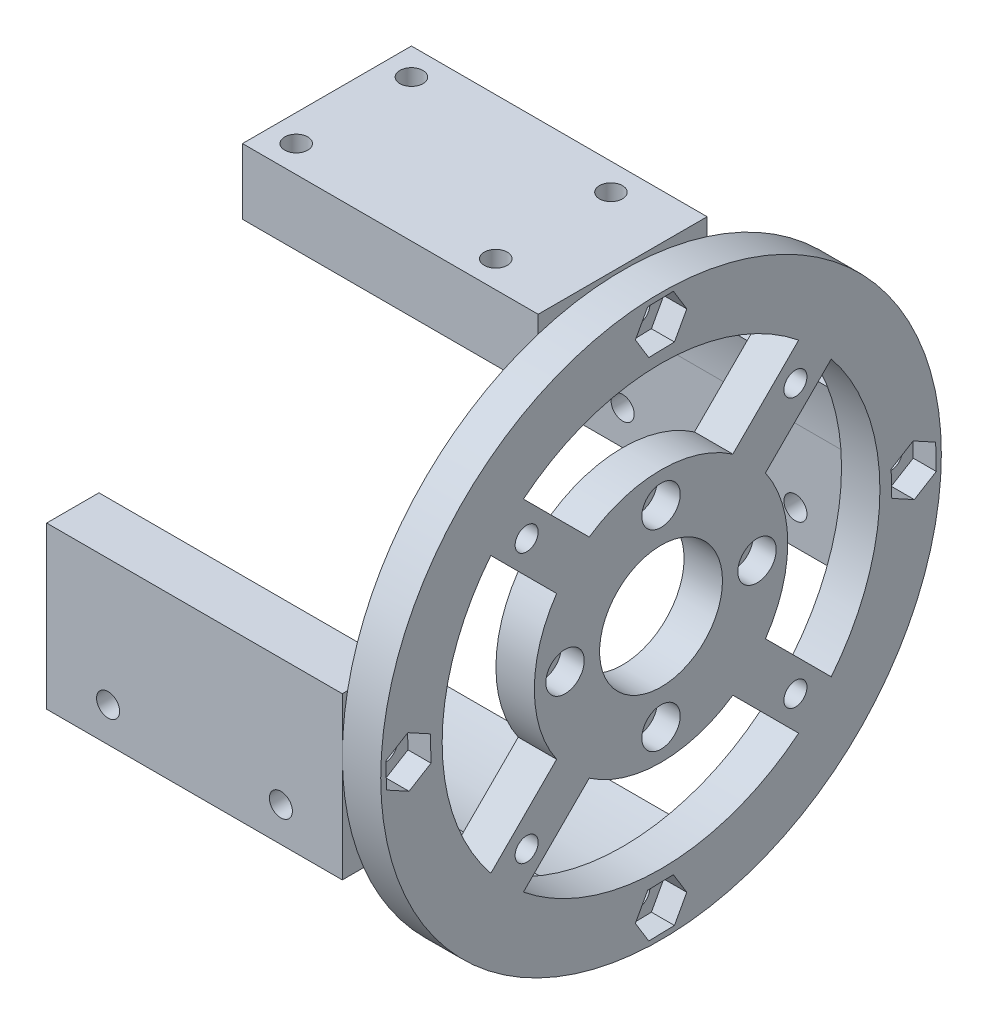
SolidWorks part; units mm, degrees
material "聚脂树脂"
ref_plane "前视基准面" through (0, 0, 0) normal (0, 0, 1) x (1, 0, 0)
ref_plane "上视基准面" through (0, 0, 0) normal (0, 1, 0) x (1, 0, 0)
ref_plane "右视基准面" through (0, 0, 0) normal (1, 0, 0) x (0, 0, -1)
sketch "草图1" plane through (0, 0, 0) normal (1, 0, 0) x (0, 0, -1)
  line L2 (13.5941, 9.3515) -> (22.1619, 17.9193)
  line L3 (9.3515, 13.5941) -> (17.9193, 22.1619)
  line L4 (13.5941, -9.3515) -> (22.1619, -17.9193)
  line L5 (9.3515, -13.5941) -> (17.9193, -22.1619)
  line L6 (-9.3515, -13.5941) -> (-17.9193, -22.1619)
  line L7 (-13.5941, -9.3515) -> (-22.1619, -17.9193)
  line L8 (-13.5941, 9.3515) -> (-22.1619, 17.9193)
  line L9 (-9.3515, 13.5941) -> (-17.9193, 22.1619)
  circle A0 centre (0, 0) radius 36.5
  circle A2 centre (0, 12.5) radius 1.55
  circle A3 centre (12.5, 0) radius 1.55
  circle A4 centre (0, -12.5) radius 1.55
  circle A5 centre (-12.5, 0) radius 1.55
  circle A6 centre (0, 0) radius 8
  arc A7 (17.9193, 22.1619) -> (-17.9193, 22.1619) centre (0, 0) ccw
  arc A8 (9.3515, 13.5941) -> (-9.3515, 13.5941) centre (0, 0) ccw
  arc A9 (-13.5941, 9.3515) -> (-13.5941, -9.3515) centre (0, 0) ccw
  arc A10 (-9.3515, -13.5941) -> (9.3515, -13.5941) centre (0, 0) ccw
  arc A14 (13.5941, -9.3515) -> (13.5941, 9.3515) centre (0, 0) ccw
  arc A15 (-22.1619, 17.9193) -> (-22.1619, -17.9193) centre (0, 0) ccw
  arc A16 (-17.9193, -22.1619) -> (17.9193, -22.1619) centre (0, 0) ccw
  arc A17 (22.1619, -17.9193) -> (22.1619, 17.9193) centre (0, 0) ccw
  point P15 (0, 0)
  point P37 (0, 0)
  dimension "73" = 73
  dimension "D3" = 3.1
  dimension "D5" = 16
  dimension "D6" = 57
  dimension "D7" = 33
  dimension "D4" = 4
  dimension "D11" = 4
extrude "凸台-拉伸1" add sketch "草图1" against normal blind 5
sketch "草图2" plane through (-5, 0, 0) normal (-1, 0, 0) x (0, 0, 1)
  line L0 (0, 30.5) -> (0, 36.5)
  line L1 (5.9179, 29.9204) -> (7.0821, 35.8063)
  line L2 (-7.0821, 35.8063) -> (-5.9179, 29.9204)
  line L3 (29.9025, -6.0076) -> (35.7885, -7.1718)
  line L4 (35.7885, 6.9924) -> (29.9025, 5.8282)
  line L5 (-6.0255, -29.9922) -> (-7.1896, -35.8781)
  line L6 (6.9745, -35.8781) -> (5.8104, -29.9922)
  line L7 (-30.01, 5.9358) -> (-35.896, 7.1)
  line L8 (-35.896, -7.0642) -> (-30.01, -5.9)
  circle A0 centre (0, 0) radius 30.5
  circle A1 centre (0, 0) radius 36.5 construction
  circle A2 centre (0, 0) radius 36.5
  point P12 (6.5, 32.8634)
  point P13 (0, 33.5)
  point P14 (-6.5, 32.8634)
  point P30 (-0.0538, -0.0359)
  dimension "D1" = 61
  dimension "D2" = 6.5
  dimension "D3" = 6.5
  dimension "D4" = 4
sketch "草图5" plane through (0, 0, 0) normal (1, 0, 0) x (0, 0, -1)
  line L0 (-0.0065, -0.0065) -> (-0.0065, -32.9065)
  circle A1 centre (-0.0065, -32.9065) radius 1.55
  circle A2 centre (-32.9, 0) radius 1.55
  circle A3 centre (0.0065, 32.8935) radius 1.55
  circle A4 centre (32.9, -0.013) radius 1.55
  point P14 (0, -0.0065)
  dimension "D2" = 3.1
  dimension "D1" = 32.9
  dimension "D3" = 4
extrude "切除-拉伸2" cut sketch "草图5" against normal up to next
sketch "草图7" plane through (0, 0, 0) normal (1, 0, 0) x (0, 0, -1)
  circle A0 centre (0.0001, -32.9065) radius 1.55
  dimension "D1" = 3.1
  dimension "D2" = 32.9
extrude "切除-拉伸3" cut sketch "草图7" against normal up to next
sketch "草图8" plane through (0, 0, 0) normal (1, 0, 0) x (0, 0, -1)
  line L30 (35.8368, -1.6063) -> (35.7573, 1.7389)
  line L31 (3.3517, 32.973) -> (1.6102, 35.8303)
  line L32 (1.6102, 35.8303) -> (-1.735, 35.7508)
  line L33 (-1.735, 35.7508) -> (-3.3387, 32.814)
  line L34 (-3.3387, 32.814) -> (-1.5973, 29.9568)
  line L35 (-1.5973, 29.9568) -> (1.7479, 30.0362)
  line L36 (1.7479, 30.0362) -> (3.3517, 32.973)
  line L43 (35.7573, 1.7389) -> (32.8206, 3.3427)
  line L44 (32.8206, 3.3427) -> (29.9633, 1.6013)
  line L45 (29.9633, 1.6013) -> (30.0428, -1.7439)
  line L46 (30.0428, -1.7439) -> (32.9795, -3.3477)
  line L47 (32.9795, -3.3477) -> (35.8368, -1.6063)
  line L48 (-1.5997, -35.8328) -> (1.7455, -35.7534)
  line L49 (1.7455, -35.7534) -> (3.3492, -32.8166)
  line L50 (3.3492, -32.8166) -> (1.6078, -29.9593)
  line L51 (1.6078, -29.9593) -> (-1.7374, -30.0388)
  line L52 (-1.7374, -30.0388) -> (-3.3411, -32.9756)
  line L53 (-3.3411, -32.9756) -> (-1.5997, -35.8328)
  line L54 (-35.8263, 1.6037) -> (-35.7468, -1.7415)
  line L55 (-35.7468, -1.7415) -> (-32.81, -3.3453)
  line L56 (-32.81, -3.3453) -> (-29.9528, -1.6038)
  line L57 (-29.9528, -1.6038) -> (-30.0322, 1.7414)
  line L58 (-30.0322, 1.7414) -> (-32.969, 3.3451)
  line L59 (-32.969, 3.3451) -> (-35.8263, 1.6037)
  circle A1 centre (0.0065, 32.8935) radius 2.8978 construction
  point P29 (0.0053, -0.0013)
  point P30 (0, 0)
  dimension "D1" = 4
extrude "切除-拉伸4" cut sketch "草图8" against normal blind 3
sketch "草图10" plane through (0, 0, 0) normal (1, 0, 0) x (0, 0, -1)
  line L5 (-17.5, -17.5) -> (17.5, 17.5) construction
  line L6 (-17.5, 17.5) -> (17.5, -17.5) construction
  circle A0 centre (-17.5, 17.5) radius 1.5
  point P0 (0, 0)
  dimension "D2" = 3
  dimension "D1" = 35
extrude "切除-拉伸5" cut sketch "草图10" against normal blind 5
pattern_circular "阵列(圆周)1" count 4 over 360 about axis through (0, 0, 0) along (1, 0, 0) of "切除-拉伸5"
sketch "草图11" plane through (-5, 0, 0) normal (-1, 0, 0) x (0, 0, 1)
  line L2 (-11, 28.5) -> (-11, 37.04)
  line L5 (0, 12.5) -> (0, 33.473) construction
  line L6 (-11, 28.5) -> (11, 28.5)
  line L7 (-11, 37.04) -> (11, 37.04)
  line L8 (11, 28.5) -> (11, 37.04)
  arc A2 (17.9193, 22.1619) -> (-17.9193, 22.1619) centre (0, 0) ccw construction
  point P15 (0, 28.5)
  point P16 (0, 37.04)
  dimension "D1" = 11
  dimension "D2" = 8.54
extrude "凸台-拉伸4" add sketch "草图11" along normal blind 38.5
sketch "草图12" plane through (-5, 0, 0) normal (-1, 0, 0) x (0, 0, 1)
  line L0 (-28.5, 7) -> (-28.5, -14)
  line L1 (-28.5, -14) -> (-36.5, -14)
  line L2 (-36.5, -14) -> (-36.5, 7)
  line L3 (-36.5, 7) -> (-28.5, 7)
  line L4 (0, 0) -> (-36.5, 0) construction
  line L5 (0, 0) -> (32.9, 0) construction
  line L6 (28.5, 7) -> (28.5, -14)
  line L7 (28.5, -14) -> (36.5, -14)
  line L8 (36.5, -14) -> (36.5, 7)
  line L9 (36.5, 7) -> (28.5, 7)
  arc A0 (-22.1619, 17.9193) -> (-22.1619, -17.9193) centre (0, 0) ccw construction
  arc A1 (22.1619, -17.9193) -> (22.1619, 17.9193) centre (0, 0) ccw construction
  arc A4 (-11, 34.803) -> (11, 34.803) centre (0, 0) ccw construction
  dimension "D1" = 14
  dimension "D2" = 14
  dimension "D3" = 7
  dimension "D6" = 7
extrude "凸台-拉伸5" add sketch "草图12" along normal blind 38.5
sketch "草图13" plane through (-5, 0, 0) normal (-1, 0, 0) x (0, 0, 1)
  line L4 (-7.1884, -27.5786) -> (-9.2062, -35.3199)
  line L5 (7.1884, -27.5786) -> (9.2062, -35.3199)
  arc A2 (-17.9193, -22.1619) -> (17.9193, -22.1619) centre (0, 0) ccw construction
  arc A3 (-33.7083, -14) -> (33.7083, -14) centre (0, 0) ccw construction
  arc A4 (-7.1884, -27.5786) -> (7.1884, -27.5786) centre (0, 0) ccw
  arc A5 (-9.2062, -35.3199) -> (9.2062, -35.3199) centre (0, 0) ccw
extrude "凸台-拉伸6" add sketch "草图13" along normal blind 38.5
sketch "草图15" plane through (0, 0, 0) normal (1, 0, 0) x (0, 0, -1)
  circle A0 centre (-32.9, 0) radius 1.55
extrude "切除-拉伸6" cut sketch "草图15" against normal blind 45
sketch "草图16" plane through (0, 0, 0) normal (1, 0, 0) x (0, 0, -1)
  circle A0 centre (-0.0032, -32.9089) radius 1.5541
  circle A1 centre (32.9, -0.013) radius 1.55
  circle A2 centre (0.0065, 32.8935) radius 1.55
extrude "切除-拉伸7" cut sketch "草图16" against normal blind 45
sketch "草图17" plane through (0, 37.04, 0) normal (0, 1, 0) x (1, 0, 0)
  line L0 (-43.5, -11) -> (-43.5, 11) construction
  line L1 (-40, -7.5) -> (-14.02, -7.5) construction
  line L3 (-14.02, 7.5) -> (-14.02, -7.5) construction
  line L5 (-40, 7.5) -> (-40, -7.5) construction
  circle A0 centre (-40, 7.5) radius 1.5
  circle A1 centre (-14.02, 7.5) radius 1.5
  circle A2 centre (-40, -7.5) radius 1.5
  circle A3 centre (-14.02, -7.5) radius 1.5
  dimension "D3" = 3.5
  dimension "D1" = 25.98
  dimension "D2" = 15
extrude "切除-拉伸8" cut sketch "草图17" against normal blind 10
sketch "草图18" plane through (0, 0, -36.5) normal (0, 0, -1) x (-1, 0, 0)
  line L1 (43.5, -14) -> (5, -14) construction
  line L2 (5, 7) -> (5, 0) construction
  line L3 (43.5, 7) -> (43.5, -14) construction
  circle A0 centre (13, -9.5) radius 1.5
  circle A1 centre (35.5, -9.5) radius 1.5
  dimension "D1" = 4.5
  dimension "D2" = 8
  dimension "D3" = 8
  dimension "D4" = 4.5
extrude "切除-拉伸9" cut sketch "草图18" against normal blind 10
sketch "草图19" plane through (0, 0, 36.5) normal (0, 0, 1) x (1, 0, 0)
  line L1 (-43.5, -14) -> (-43.5, 7) construction
  line L2 (-5, -14) -> (-5, 0) construction
  line L3 (-43.5, -14) -> (-5, -14) construction
  circle A0 centre (-35.5, -9.5) radius 1.5
  circle A1 centre (-13, -9.5) radius 1.5
  dimension "D1" = 8
  dimension "D2" = 8
  dimension "D3" = 4.5
  dimension "D4" = 4.5
extrude "切除-拉伸10" cut sketch "草图19" against normal blind 10
sketch "草图20" plane through (0, 28.5, 0) normal (0, -1, 0) x (1, 0, 0)
  line L0 (-43.5, 9.2062) -> (-43.5, -9.2062) construction
  line L1 (-40, 7.5) -> (-40, -7.5) construction
  line L2 (-14.02, 7.5) -> (-14.02, -7.5) construction
  line L3 (-40, -7.5) -> (-14.02, -7.5) construction
  line L4 (-40, 7.5) -> (-14.02, 7.5) construction
  line L5 (-43.5, 11) -> (-5, 11) construction
  circle A0 centre (-40, 7.5) radius 2.5
  circle A1 centre (-14.02, 7.5) radius 2.5
  circle A2 centre (-14.02, -7.5) radius 2.5
  circle A3 centre (-40, -7.5) radius 2.5
  dimension "D1" = 3.5
  dimension "D2" = 15
  dimension "D3" = 3.5
  dimension "D4" = 25.98
extrude "切除-拉伸11" cut sketch "草图20" against normal blind 4
sketch "草图21" plane through (0, 0, 0) normal (1, 0, 0) x (0, 0, -1)
  circle A0 centre (-12.5, 0) radius 2.5
  circle A1 centre (12.5, 0) radius 2.5
  circle A2 centre (0, 12.5) radius 2.5
  circle A3 centre (0, -12.5) radius 2.5
extrude "切除-拉伸12" cut sketch "草图21" against normal blind 3
sketch "草图23" plane through (-5, 0, 0) normal (-1, 0, 0) x (0, 0, 1)
  circle A0 centre (0, 0) radius 30.5
extrude "切除-拉伸13" cut sketch "草图23" along normal blind 41
sketch "草图27" plane through (-5, 0, 0) normal (-1, 0, 0) x (0, 0, 1)
  line L0 (-30.5, 0) -> (-30.5, -14)
  line L1 (-36.5, -14) -> (-28.5, -14) construction
  line L2 (-30.5, -14) -> (-28.5, -14)
  line L3 (-28.5, -14) -> (-28.5, -10.8628)
  line L4 (30.5, 0) -> (30.5, -14)
  line L5 (28.5, -14) -> (33.7083, -14) construction
  line L6 (30.5, -14) -> (28.5, -14)
  line L7 (28.5, -14) -> (28.5, -10.8628)
  arc A0 (-29.6859, 7) -> (-28.5, -10.8628) centre (0, 0) ccw construction
  arc A1 (-29.6859, 7) -> (-28.5, -10.8628) centre (0, 0) ccw construction
  arc A2 (-28.5, -10.8628) -> (-30.5, 0) centre (0, 0) cw
  arc A3 (28.5, -10.8628) -> (29.6859, 7) centre (0, 0) ccw construction
  arc A4 (30.5, 0) -> (28.5, -10.8628) centre (0, 0) cw
extrude "切除-拉伸15" cut sketch "草图27" along normal through all
